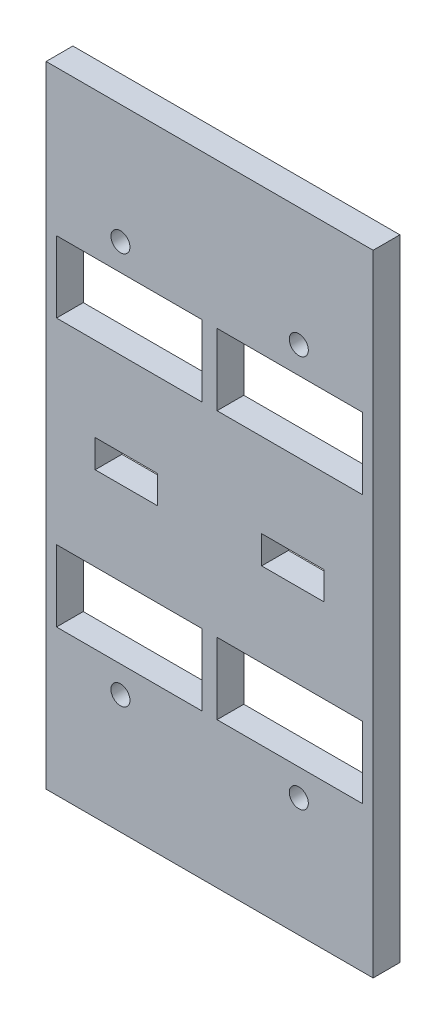
SolidWorks part; units mm, degrees
ref_plane "Front Plane" through (0, 0, 0) normal (0, 0, 1) x (1, 0, 0)
ref_plane "Top Plane" through (0, 0, 0) normal (0, 1, 0) x (1, 0, 0)
ref_plane "Right Plane" through (0, 0, 0) normal (1, 0, 0) x (0, 0, -1)
sketch "Sketch1" plane through (0, 0, 0) normal (0, 0, 1) x (1, 0, 0)
  line L0 (0, -53) -> (0, 53) construction
  line L1 (-27.5, -53) -> (27.5, -53)
  line L2 (-27.5, -53) -> (-27.5, 53)
  line L3 (-27.5, 53) -> (27.5, 53)
  line L4 (27.5, -53) -> (27.5, 53)
  line L5 (-27.5, -53) -> (27.5, 53) construction
  line L6 (-27.5, 53) -> (27.5, -53) construction
  line L7 (-27.5, 0) -> (27.5, 0) construction
  line L8 (-27.5, 22.5) -> (27.5, 22.5) construction
  line L9 (25.75, 16.5) -> (1.25, 28.5) construction
  line L10 (-25.75, 28.5) -> (-1.25, 28.5)
  line L11 (-25.75, 28.5) -> (-25.75, 16.5)
  line L12 (-25.75, 16.5) -> (-1.25, 16.5)
  line L13 (-1.25, 28.5) -> (-1.25, 16.5)
  line L14 (-25.75, 28.5) -> (-1.25, 16.5) construction
  line L15 (-25.75, 16.5) -> (-1.25, 28.5) construction
  line L16 (25.75, 28.5) -> (1.25, 16.5) construction
  line L17 (1.25, 28.5) -> (1.25, 16.5)
  line L18 (25.75, 16.5) -> (1.25, 16.5)
  line L19 (25.75, 28.5) -> (25.75, 16.5)
  line L20 (25.75, 28.5) -> (1.25, 28.5)
  line L21 (25.75, -28.5) -> (1.25, -16.5) construction
  line L22 (-25.75, -16.5) -> (-1.25, -28.5) construction
  line L23 (-25.75, -28.5) -> (-1.25, -16.5) construction
  line L24 (25.75, -16.5) -> (1.25, -28.5) construction
  line L25 (25.75, -28.5) -> (1.25, -28.5)
  line L26 (25.75, -28.5) -> (25.75, -16.5)
  line L27 (25.75, -16.5) -> (1.25, -16.5)
  line L28 (1.25, -28.5) -> (1.25, -16.5)
  line L29 (-1.25, -28.5) -> (-1.25, -16.5)
  line L30 (-25.75, -16.5) -> (-1.25, -16.5)
  line L31 (-25.75, -28.5) -> (-25.75, -16.5)
  line L32 (-25.75, -28.5) -> (-1.25, -28.5)
  point P0 (0, 0)
  point P12 (-13.5, 22.5)
  point P21 (13.5, 22.5)
  point P30 (13.5, -22.5)
  point P31 (-13.5, -22.5)
  dimension "D1" = 55
  dimension "D2" = 106
  dimension "D3" = 22.5
  dimension "D4" = 24.5
  dimension "D5" = 12
  dimension "D6" = 1.25
extrude "Boss-Extrude1" add sketch "Sketch1" along normal blind 4.5
sketch "Sketch2" plane through (0, 0, 4.5) normal (0, 0, 1) x (1, 0, 0)
  line L0 (0, -53) -> (0, 53) construction
  line L1 (-27.5, -53) -> (27.5, -53) construction
  line L2 (27.5, 53) -> (-27.5, 53) construction
  line L3 (-27.5, 0) -> (27.5, 0) construction
  line L4 (-27.5, 53) -> (-27.5, -53) construction
  line L5 (27.5, -53) -> (27.5, 53) construction
  circle A0 centre (-15, 33) radius 1.6
  circle A1 centre (15, 33) radius 1.6
  circle A2 centre (15, -33) radius 1.6
  circle A3 centre (-15, -33) radius 1.6
  dimension "D1" = 3.2
  dimension "D2" = 15
  dimension "D3" = 33
extrude "Cut-Extrude1" cut sketch "Sketch2" against normal through all
sketch "Sketch3" plane through (0, 0, 4.5) normal (0, 0, 1) x (1, 0, 0)
  line L0 (-27.5, 0) -> (27.5, 0) construction
  line L1 (-27.5, 53) -> (-27.5, -53) construction
  line L2 (27.5, -53) -> (27.5, 53) construction
  line L3 (0, 53) -> (0, -53) construction
  line L4 (27.5, 53) -> (-27.5, 53) construction
  line L5 (-27.5, -53) -> (27.5, -53) construction
  line L6 (19.25, -2.35) -> (8.75, 2.35) construction
  line L7 (-19.25, 2.35) -> (-8.75, 2.35)
  line L8 (-19.25, 2.35) -> (-19.25, -2.35)
  line L9 (-19.25, -2.35) -> (-8.75, -2.35)
  line L10 (-8.75, 2.35) -> (-8.75, -2.35)
  line L11 (-19.25, 2.35) -> (-8.75, -2.35) construction
  line L12 (-19.25, -2.35) -> (-8.75, 2.35) construction
  line L13 (19.25, 2.35) -> (8.75, -2.35) construction
  line L14 (8.75, 2.35) -> (8.75, -2.35)
  line L15 (19.25, -2.35) -> (8.75, -2.35)
  line L16 (19.25, 2.35) -> (19.25, -2.35)
  line L17 (19.25, 2.35) -> (8.75, 2.35)
  point P12 (-14, 0)
  point P21 (14, 0)
  dimension "D1" = 10.5
  dimension "D2" = 4.7
  dimension "D3" = 14
extrude "Cut-Extrude2" cut sketch "Sketch3" against normal through all
equation "\"X-ROD-SPACING\"=45"
equation "\"Y-ROD-SPACING\"=75"
equation "\"Z-ROD-SPACING\"=17.5"
equation "\"Y-BED-OFFSET\"=0"
equation "\"Y-BED-ROD-INSET\"=3.5"
equation "\"Y-BED-SCREW-SPACING\"=209"
equation "\"Y-BED-SCREW-CUTOUT-SLOT-HEIGHT\"=1"
equation "\"T-SLOT-NUT-FILLET-RADIUS\"=0.25"
equation "\"T-SLOT-SCREW-SHAFT-RADIUS\"=1.75"
equation "\"T-SLOT-SCREW-SHAFT-CUTOUT-LENGTH\"=10.5"
equation "\"T-SLOT-NUT-DEPTH\"=4.2"
equation "\"T-SLOT-NUT-WIDTH\"=3"
equation "\"T-SLOT-NUT-END-DISTANCE\"=8"
equation "\"ACRYLIC-THICKNESS\"=10"
equation "\"ACRYLIC-THICKNESS2\"=4.5"
equation "\"ACRYLIC-TAB-CUTOUT-SIZE\"=\"ACRYLIC-THICKNESS\"+.5"
equation "\"ACRYLIC-TAB-WIDTH\"=\"ACRYLIC-THICKNESS\""
equation "\"ACRYLIC-M3-HOLE\"=3.2"
equation "\"SMOOTHROD-CAP-SCREW-DISTANCE\"=20"
equation "\"FRAME-WIDTH-INNER\"=370"
equation "\"NEMA17-HOLE-SPACING\"=31"
equation "\"NEMA17-CENTRAL-CUTOUT\"=22.5"
equation "\"Z-BRACKET-REACH\"=55"
equation "\"Z-ROD-INSET\"=16"
equation "\"TOP-BRACKET-SPACING\"=40"
equation "\"SMOOTHROD-X-LENGTH\"=350"
equation "\"SMOOTHROD-Y-LENGTH\"=350"
equation "\"SMOOTHROD-Z-LENGTH\"=350"
equation "\"SMOOTHROD-TIGHTENING-HEADROOM\"=1"
equation "\"LEADSCREW-Z-LENGTH\"=300"
equation "\"SCREW-LENGTH-FRAME\"=\"ACRYLIC-THICKNESS\" + 10"
equation "\"SCREW-LENGTH-MOTOR\"=\"ACRYLIC-THICKNESS\" + 5"
equation "\"SCREW-HEAD-RADIUS\"=6"
equation "\"PRINTED-X-SMOOTHROD-DIAMETER\"=8.2"
equation "\"PRINTED-X-SMOOTHROD-CUTOUT\"=10"
equation "\"PRINTED-X-BASE-HEIGHT\"=10"
equation "\"PRINTED-LM8UU-CUTOUT-SIZE\"=16"
equation "\"PRINTED-LM8UU-CUTOUT-LENGTH\"=24.5"
equation "\"PRINTED-X-IDLER-HEIGHT\"=16"
equation "\"PSU-MOUNTING-WIDTH\"=95"
equation "\"PSU-MOUNTING-HEIGHT\"=177"
equation "\"Y-BELT-TO-ROD-DISTANCE\"=20"
equation "\"SPOOL-HOLDER-ROD-SPACING\"=150"
equation "\"D3@Sketch1\"=\"X-ROD-SPACING\"/2"
equation "\"D4@Sketch1\"=\"PRINTED-LM8UU-CUTOUT-LENGTH\""
equation "\"D1@Boss-Extrude1\"=\"ACRYLIC-THICKNESS2\""
equation "\"D1@Sketch2\"=\"ACRYLIC-M3-HOLE\""
equation "\"D1@Sketch3\"=\"ACRYLIC-TAB-CUTOUT-SIZE\""
equation "\"D2@Sketch3\"=\"ACRYLIC-THICKNESS2\"+.2"
equation "\"ACRYLIC-X-CARRIAGE-WIDTH\"=55"
equation "\"ACRYLIC-X-CARRIAGE-HEIGHT\"=106"
equation "\"D2@Sketch1\"=\"ACRYLIC-X-CARRIAGE-HEIGHT\""
equation "\"D1@Sketch1\"=\"ACRYLIC-X-CARRIAGE-WIDTH\""
equation "\"ACRYLIC-X-CARRIAGE-CENTER-TAB-SPACING\"=14"
equation "\"D3@Sketch3\"=\"ACRYLIC-X-CARRIAGE-CENTER-TAB-SPACING\""
equation "\"SCREW-LENGTH-EXTRUDER\"=28"
equation "\"ACRYLIC-X-CARRIAGE-SCREW-SPACING-X\"=15"
equation "\"ACRYLIC-X-CARRIAGE-SCREW-SPACING-Y\"=33"
equation "\"D2@Sketch2\"=\"ACRYLIC-X-CARRIAGE-SCREW-SPACING-X\""
equation "\"D3@Sketch2\"=\"ACRYLIC-X-CARRIAGE-SCREW-SPACING-Y\""
